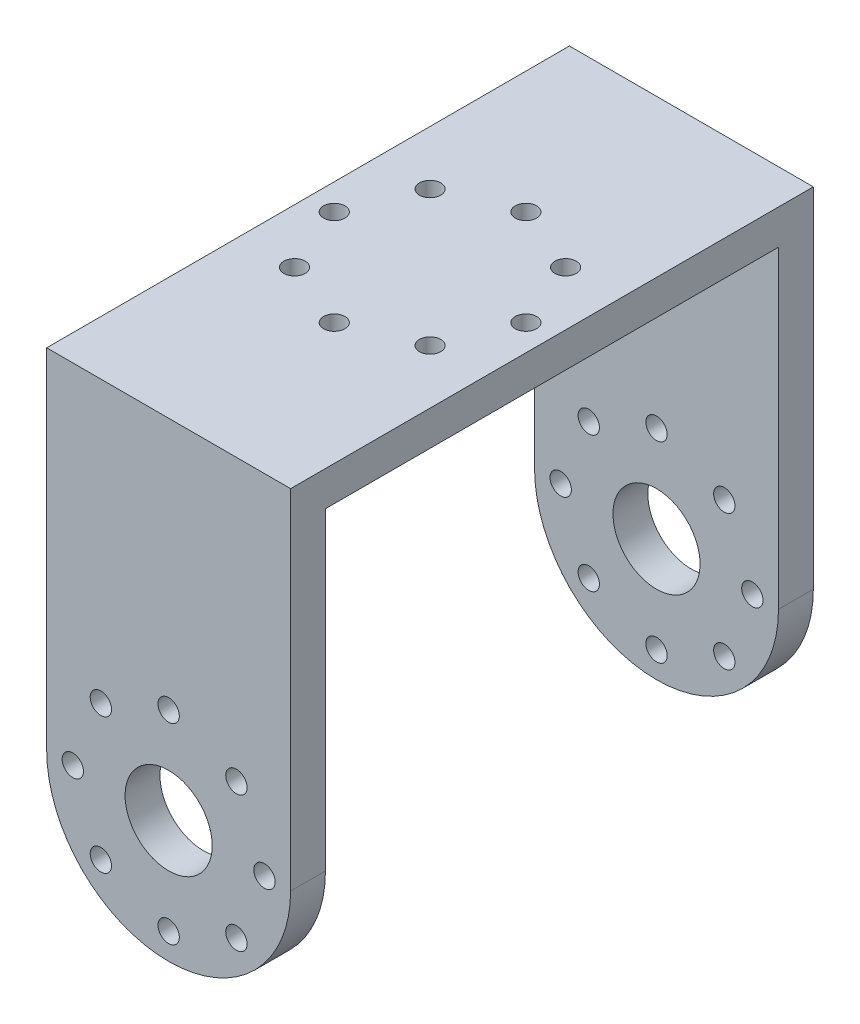
SolidWorks part; units mm, degrees
ref_plane "정면" through (0, 0, 0) normal (0, 0, 1) x (1, 0, 0)
ref_plane "윗면" through (0, 0, 0) normal (0, 1, 0) x (1, 0, 0)
ref_plane "우측면" through (0, 0, 0) normal (1, 0, 0) x (0, 0, -1)
sketch "스케치2" plane through (0, 0, 0) normal (0, 0, 1) x (1, 0, 0)
  line L2 (-14, 0) -> (-14, 40)
  line L3 (-14, 40) -> (14, 40)
  line L4 (14, 0) -> (14, 40)
  arc A0 (-14, 0) -> (14, 0) centre (0, 0) ccw
  circle A18 centre (0, 0) radius 5
  circle A20 centre (0, 11) radius 1.225
  circle A22 centre (7.7782, 7.7782) radius 1.225
  circle A24 centre (11, 0) radius 1.225
  circle A25 centre (7.7782, -7.7782) radius 1.225
  circle A27 centre (0, -11) radius 1.225
  circle A28 centre (-7.7782, -7.7782) radius 1.225
  circle A30 centre (-11, 0) radius 1.225
  circle A31 centre (-7.7782, 7.7782) radius 1.225
  dimension "D1" = 10
  dimension "D3" = 2.45
  dimension "D5" = 14
  dimension "D2" = 40
  dimension "D4" = 11
  dimension "D7" = 7.7782
  dimension "D9" = 11
  dimension "D11" = 7.7782
  dimension "D14" = 7.7782
  dimension "D15" = 11
  dimension "D16" = 7.7782
  dimension "D18" = 11
extrude "보스-돌출1" add sketch "스케치2" along normal blind 60
sketch "스케치9" plane through (14, 0, 0) normal (1, 0, 0) x (0, 0, -1)
  line L0 (-60, -14) -> (0, -14) construction
  line L1 (-56, 36) -> (-4, 36)
  line L2 (-56, 36) -> (-56, -14)
  line L3 (-56, -14) -> (-4, -14)
  line L4 (-4, 36) -> (-4, -14)
  line L5 (-60, 40) -> (0, 40) construction
  line L6 (-60, 0) -> (-60, 40) construction
  line L7 (0, 0) -> (0, 40) construction
  dimension "D1" = 4
  dimension "D2" = 4
  dimension "D3" = 4
  dimension "D4" = 52
extrude "컷-돌출1" cut sketch "스케치9" against normal blind 60
sketch "스케치10" plane through (0, 40, 0) normal (0, 1, 0) x (1, 0, 0)
  line L0 (0, 0) -> (0, -60) construction
  line L1 (14, -60) -> (-14, -60) construction
  line L2 (14, -30) -> (-14, -30) construction
  line L3 (14, -60) -> (14, 0) construction
  line L4 (-14, -60) -> (-14, 0) construction
  line L5 (14, 0) -> (-14, 0) construction
  circle A0 centre (-7.7748, -22.2155) radius 1.225
  circle A1 centre (0.0034, -18.9937) radius 1.225
  circle A2 centre (7.7816, -22.2155) radius 1.225
  circle A3 centre (11.0034, -29.9937) radius 1.225
  circle A4 centre (7.7816, -37.7718) radius 1.225
  circle A5 centre (0.0034, -40.9937) radius 1.225
  circle A6 centre (-7.7748, -37.7718) radius 1.225
  circle A7 centre (-10.9966, -29.9937) radius 1.225
  dimension "D1" = 2.45
  dimension "D2" = 3.0034
  dimension "D3" = 6.2252
  dimension "D4" = 14.0034
  dimension "D5" = 21.7816
  dimension "D6" = 25.0034
  dimension "D7" = 18.9937
  dimension "D8" = 22.2155
  dimension "D9" = 29.9937
  dimension "D10" = 37.7718
  dimension "D11" = 40.9937
extrude "컷-돌출2" cut sketch "스케치10" against normal blind 60
